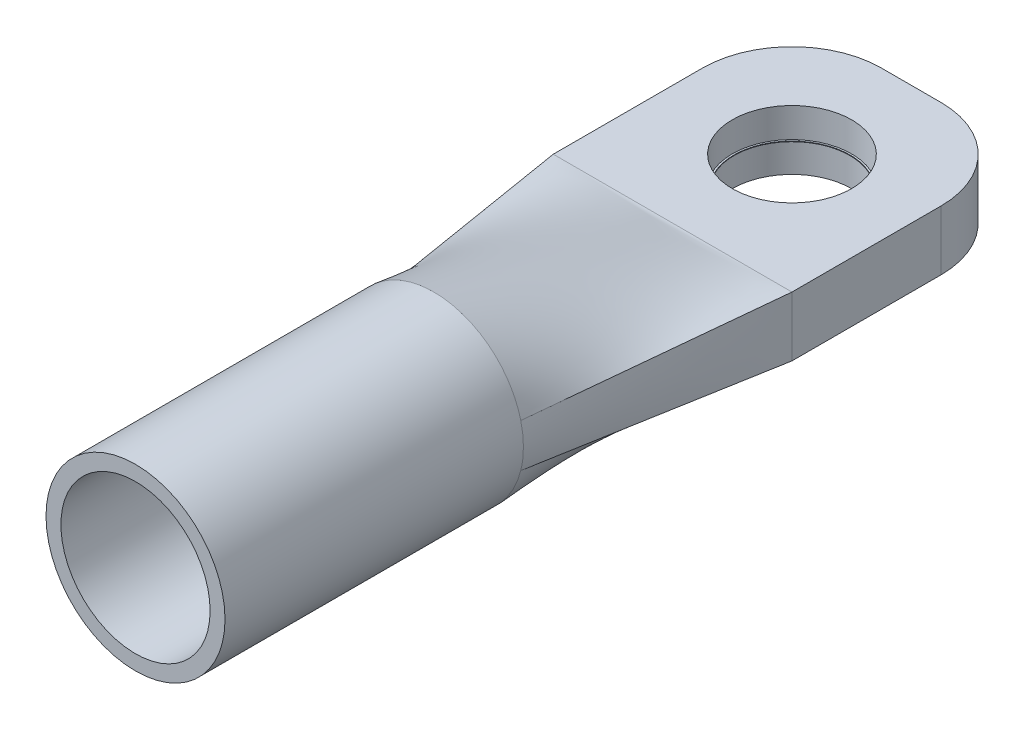
SolidWorks part; units mm, degrees
ref_plane "Plan de face" through (0, 0, 0) normal (0, 0, 1) x (1, 0, 0)
ref_plane "Plan de dessus" through (0, 0, 0) normal (0, 1, 0) x (1, 0, 0)
ref_plane "Plan de droite" through (0, 0, 0) normal (1, 0, 0) x (0, 0, -1)
sketch "Esquisse1" plane through (0, 0, 0) normal (0, 0, 1) x (1, 0, 0)
  circle A0 centre (0, 0) radius 3
  circle A1 centre (0, 0) radius 2.5
  dimension "D1" = 6
  dimension "D2" = 5
extrude "Boss.-Extru.1" add sketch "Esquisse1" along normal blind 10
ref_plane "Plan1" through (0, 0, -8) normal (0, 0, 1) x (1, 0, 0)
sketch "Esquisse3" plane through (0, 0, 0) normal (0, 0, -1) x (-1, 0, 0)
  circle A0 centre (0, 0) radius 3
sketch "Esquisse2" plane through (0, 0, -8) normal (0, 0, 1) x (1, 0, 0)
  line L1 (4, 1) -> (-4, 1)
  line L2 (4, 1) -> (4, -1)
  line L3 (4, -1) -> (-4, -1)
  line L4 (-4, 1) -> (-4, -1)
  line L5 (4, 1) -> (-4, -1) construction
  line L6 (4, -1) -> (-4, 1) construction
  point P0 (0, 0)
  dimension "D1" = 8
  dimension "D2" = 2
loft "Lissage3" add profiles "Esquisse3", "Esquisse2"
sketch "Esquisse4" plane through (0, 0, -8) normal (0, 0, -1) x (-1, 0, 0)
  line L7 (4, 1) -> (-4, 1)
  line L8 (4, 1) -> (4, -1)
  line L9 (4, -1) -> (-4, -1)
  line L10 (-4, 1) -> (-4, -1)
  line L11 (4, 1) -> (-4, -1) construction
  line L12 (4, -1) -> (-4, 1) construction
  point P9 (0, 0)
  dimension "D1" = 2
  dimension "D2" = 8
extrude "Boss.-Extru.2" add sketch "Esquisse4" along normal blind 8
fillet "Congé1" radius 3 2 edges at (-4, 0, -16) (4, 0, -16)
sketch "Esquisse6" plane through (0, 1, 0) normal (0, 1, 0) x (1, 0, 0)
  line L0 (-1, 16) -> (1, 16) construction
  circle A0 centre (0, 12) radius 2
  point P2 (0, 16)
  dimension "D1" = 4
  dimension "D2" = 4
extrude "Enlèv. mat.-Extru.2" cut sketch "Esquisse6" against normal blind 12 contours A0
sketch "Esquisse7" plane through (0, 0, 0) normal (0, 1, 0) x (1, 0, 0)
  circle A0 centre (0, 12) radius 2
  circle A1 centre (0, 12) radius 1.9426
extrude "Boss.-Extru.3" add sketch "Esquisse7" along normal blind 0.01 and the other way blind 0.01
sketch "Esquisse8" plane through (0, 0, 0) normal (0, 1, 0) x (1, 0, 0)
  point P0 (0, 12)
